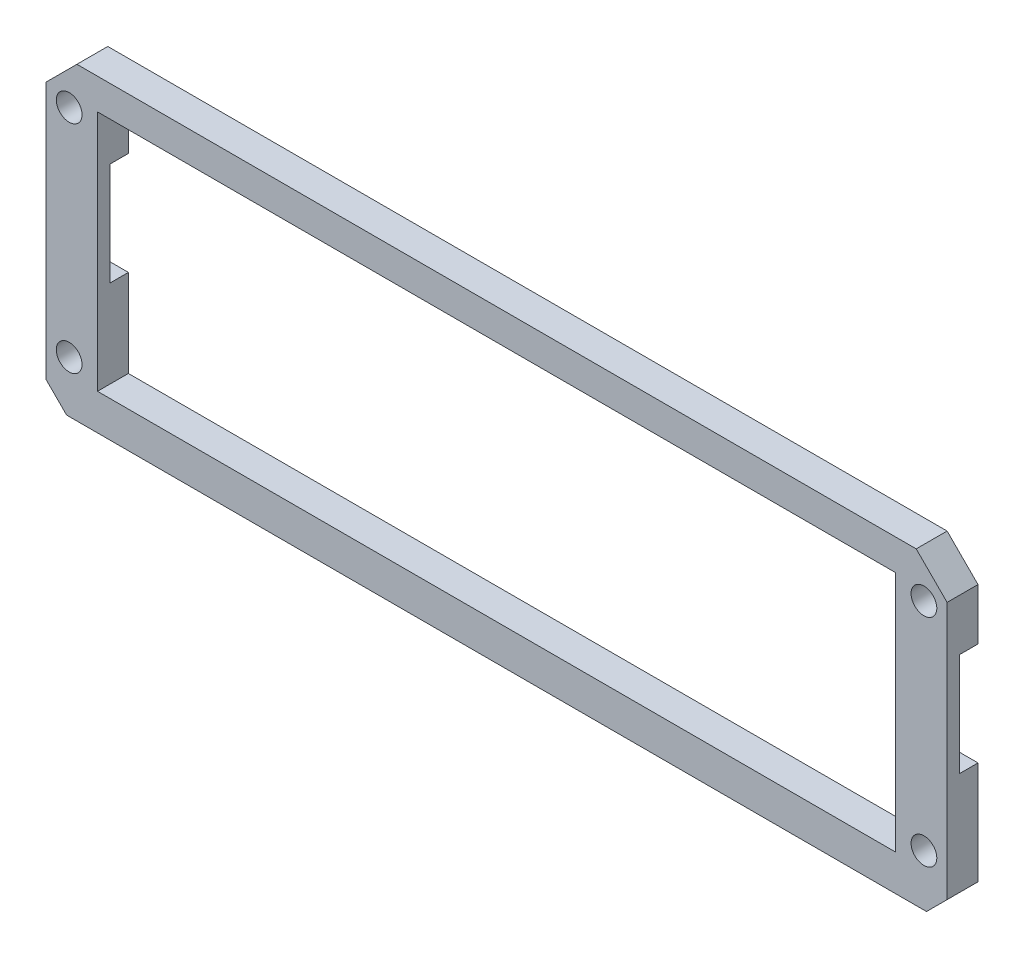
SolidWorks part; units mm, degrees
material "Thornel Mat VMA"
ref_plane "前视基准面" through (0, 0, 0) normal (0, 0, 1) x (1, 0, 0)
ref_plane "上视基准面" through (0, 0, 0) normal (0, 1, 0) x (1, 0, 0)
ref_plane "右视基准面" through (0, 0, 0) normal (1, 0, 0) x (0, 0, -1)
sketch "草图1" plane through (0, 0, 0) normal (0, 0, 1) x (1, 0, 0)
  line L1 (-43.4838, 11.9998) -> (44.0162, 11.9998)
  line L2 (-43.4838, 11.9998) -> (-43.4838, -16.0002)
  line L3 (-43.4838, -16.0002) -> (44.0162, -16.0002)
  line L4 (44.0162, 11.9998) -> (44.0162, -16.0002)
  dimension "D1" = 87.5
  dimension "D2" = 28
extrude "凸台-拉伸1" add sketch "草图1" along normal blind 3
sketch "草图2" plane through (0, 0, 3) normal (0, 0, 1) x (1, 0, 0)
  line L0 (44.0162, 11.9998) -> (-43.4838, 11.9998) construction
  line L1 (-38.4838, 11.9998) -> (39.0162, 11.9998)
  line L2 (-38.4838, 11.9998) -> (-38.4838, -10.5002)
  line L3 (-38.4838, -10.5002) -> (39.0162, -10.5002)
  line L4 (39.0162, 11.9998) -> (39.0162, -10.5002)
  line L5 (-43.4838, 11.9998) -> (-43.4838, -16.0002) construction
  line L6 (-43.4838, -16.0002) -> (44.0162, -16.0002) construction
  line L7 (44.0162, -16.0002) -> (44.0162, 11.9998) construction
  circle A0 centre (-41.2338, 7.9998) radius 1.25
  circle A1 centre (-41.2338, -13.0002) radius 1.25
  circle A2 centre (41.7662, -13.0002) radius 1.25
  circle A3 centre (41.7662, 7.9998) radius 1.25
  point P10 (-41.2338, -13.0002)
  point P11 (-41.2338, 7.9998)
  point P12 (41.7662, 7.9998)
  point P13 (41.7662, -13.0002)
  dimension "D12" = 2.5
  dimension "D1" = 77.5
  dimension "D2" = 5
  dimension "D3" = 5.5
  dimension "D4" = 2.25
  dimension "D5" = 3
  dimension "D6" = 4
  dimension "D7" = 2.25
  dimension "D8" = 2.25
  dimension "D9" = 4
  dimension "D10" = 2.25
  dimension "D11" = 3
extrude "切除-拉伸1" cut sketch "草图2" against normal blind 44
sketch3d "3D草图2" plane through (0, 0, 0) normal (0, 0, 1) x (1, 0, 0)
chamfer "倒角1" distance 1 angle 45 2 edges at (44.0162, -16.0002, 1.5) (-43.4838, -16.0002, 1.5)
sketch "草图4" plane through (44.0162, 0, 0) normal (1, 0, 0) x (0, 0, -1)
  line L0 (0, 16.5) -> (0, -16.5) construction
  line L1 (0, 3.9998) -> (-1.8, 3.9998)
  line L2 (0, 3.9998) -> (0, -6.0002)
  line L3 (0, -6.0002) -> (-1.8, -6.0002)
  line L4 (-1.8, 3.9998) -> (-1.8, -6.0002)
  line L5 (0, -16.0002) -> (-3, -16.0002) construction
  dimension "D1" = 1.8
  dimension "D2" = 10
  dimension "D3" = 10
extrude "切除-拉伸2" cut sketch "草图4" against normal blind 92
sketch "草图5" plane through (44.0162, 0, 0) normal (1, 0, 0) x (0, 0, -1)
  line L0 (0, 16.5) -> (0, -16.5) construction
  line L1 (-3, 11.9998) -> (0, 11.9998)
  line L2 (-3, 11.9998) -> (-3, 14.9998)
  line L3 (-3, 14.9998) -> (0, 14.9998)
  line L4 (0, 11.9998) -> (0, 14.9998)
  line L5 (0, -16.0002) -> (-3, -16.0002) construction
  dimension "D1" = 31
extrude "凸台-拉伸2" add sketch "草图5" against normal blind 87.5 contours L3 L4 L1 L2
sketch "草图7" plane through (0, 0, 0) normal (0, 0, -1) x (-1, 0, 0)
  line L0 (-44.0162, -15.0002) -> (-44.0162, -18.0002)
  line L1 (-44.0162, -18.0002) -> (43.4838, -18.0002)
  line L2 (43.4838, -18.0002) -> (43.4838, -15.0002)
  line L3 (43.4838, -15.0002) -> (42.9838, -15.5002)
  line L4 (42.4838, -16.0002) -> (43.4838, -15.0002) construction
  line L5 (42.9838, -15.5002) -> (-43.0162, -16.0002)
  line L6 (-43.0162, -16.0002) -> (-44.0162, -15.0002)
  dimension "D1" = 3
extrude "凸台-拉伸3" add sketch "草图7" against normal up to surface (3 mm away) up to face at (0.2662, -5.3335, 3)
sketch "草图8" plane through (0, -10.5002, 0) normal (0, 1, 0) x (1, 0, 0)
  line L1 (-38.4838, 0) -> (39.0162, 0)
  line L2 (-38.4838, 0) -> (-38.4838, -3)
  line L3 (-38.4838, -3) -> (39.0162, -3)
  line L4 (39.0162, 0) -> (39.0162, -3)
extrude "切除-拉伸3" cut sketch "草图8" against normal blind 4
chamfer "倒角3" distance 2 angle 45 2 edges at (44.0162, -18.0002, 1.5) (-43.4838, -18.0002, 1.5)
sketch "草图9" plane through (0, 11.9998, 0) normal (0, -1, 0) x (1, 0, 0)
  line L1 (-38.4838, 3) -> (39.0162, 3)
  line L2 (-38.4838, 3) -> (-38.4838, 0)
  line L3 (-38.4838, 0) -> (39.0162, 0)
  line L4 (39.0162, 3) -> (39.0162, 0)
extrude "凸台-拉伸4" add sketch "草图9" along normal blind 3
sketch "草图10" plane through (0, 14.9998, 0) normal (0, 1, 0) x (1, 0, 0)
  line L1 (-43.4838, 0) -> (44.0162, 0)
  line L2 (-43.4838, 0) -> (-43.4838, -3)
  line L3 (-43.4838, -3) -> (44.0162, -3)
  line L4 (44.0162, 0) -> (44.0162, -3)
extrude "切除-拉伸4" cut sketch "草图10" against normal blind 3
chamfer "倒角4" distance 3 angle 45 2 edges at (44.0162, 11.9998, 1.5) (-43.4838, 11.9998, 1.5)
